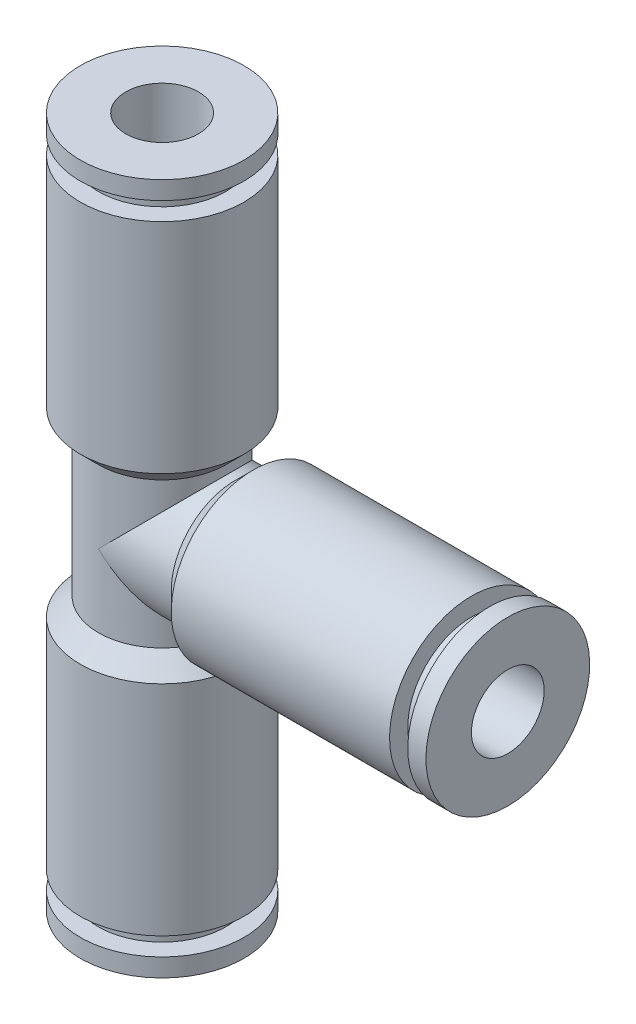
SolidWorks part; units mm, degrees
ref_plane "Спереди" through (0, 0, 0) normal (0, 0, 1) x (1, 0, 0)
ref_plane "Сверху" through (0, 0, 0) normal (0, 1, 0) x (1, 0, 0)
ref_plane "Справа" through (0, 0, 0) normal (1, 0, 0) x (0, 0, -1)
sketch "Эскиз1" plane through (0, 0, 0) normal (0, 0, 1) x (1, 0, 0)
  line L0 (0, 0.8873) -> (0, 23.3873) construction
  line L1 (2, 19) -> (4.5, 19)
  line L3 (-4.5, 5) -> (-4.5, 17)
  line L4 (-4.5, 17) -> (-3.5, 17)
  line L5 (4.5, 5) -> (4.5, 17)
  line L7 (-3.5, 17) -> (-3.5, 18)
  line L9 (3.5, 17) -> (3.5, 18)
  line L10 (-4.5, 19) -> (-2, 19)
  line L11 (-4.5, 19) -> (-4.5, 18)
  line L12 (-4.5, 18) -> (-3.5, 18)
  line L13 (4.5, 19) -> (4.5, 18)
  line L15 (-2, 19) -> (-2, 6)
  line L17 (2, 19) -> (2, 6)
  line L19 (3.5, 18) -> (4.5, 18)
  line L20 (3.5, 17) -> (4.5, 17)
  line L22 (-2, 19) -> (2, 19)
  line L25 (-3.5, 4) -> (-3.5, 0)
  line L27 (3.5, 4) -> (3.5, 0)
  line L28 (-4.5, 5) -> (-3.5, 4)
  line L29 (-2, 6) -> (-2, 0)
  line L30 (2, 6) -> (2, 0)
  line L31 (4.5, 5) -> (3.5, 4)
  arc A0 (-3.5, 0) -> (3.5, 0) centre (0, 0) ccw
  arc A1 (-2, 0) -> (2, 0) centre (0, 0) ccw
  dimension "D9" = 45
  dimension "D1" = 19
  dimension "D2" = 1
  dimension "D3" = 1
  dimension "D4" = 2.5
  dimension "D5" = 1
  dimension "D6" = 4
  dimension "D7" = 4
  dimension "D8" = 1
revolve "Повернуть1" add sketch "Эскиз1" angle 360 about L0
sketch "Эскиз2" plane through (0, 0, 0) normal (0, 1, 0) x (1, 0, 0)
  line L0 (0, 7.5614) -> (0, -8.0562) construction
pattern_circular "Круговой массив1" count 3 every 90 about axis through (0, 0, 0) along (0, 0, 1) of "Повернуть1"
